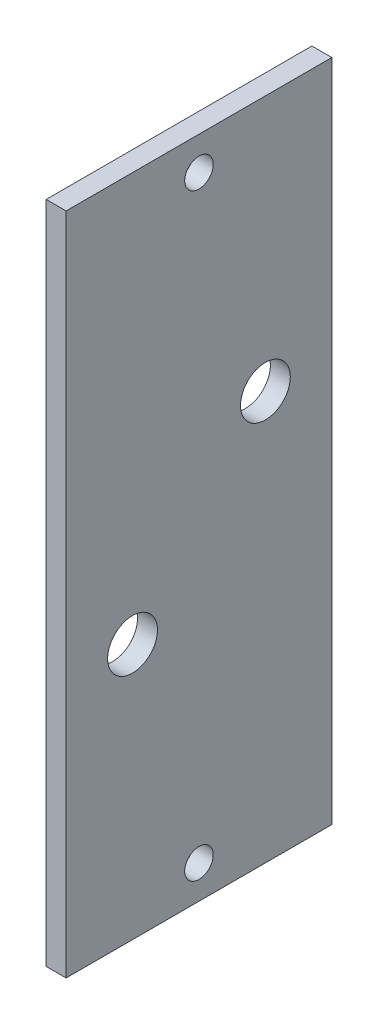
SolidWorks part; units mm, degrees
ref_plane "Front Plane" through (0, 0, 0) normal (0, 0, 1) x (1, 0, 0)
ref_plane "Top Plane" through (0, 0, 0) normal (0, 1, 0) x (1, 0, 0)
ref_plane "Right Plane" through (0, 0, 0) normal (1, 0, 0) x (0, 0, -1)
sketch "Sketch1" plane through (0, 0, 0) normal (1, 0, 0) x (0, 0, -1)
  line L0 (20, 100) -> (20, 0) construction
  line L1 (0, 0) -> (40, 0)
  line L2 (0, 0) -> (0, 100)
  line L3 (0, 100) -> (40, 100)
  line L4 (40, 0) -> (40, 100)
  line L5 (0, 50) -> (40, 50) construction
  circle A0 centre (20, 95) radius 2.15
  circle A1 centre (20, 5) radius 2.15
  circle A2 centre (10, 38.5) radius 3.75
  circle A3 centre (30, 61.5) radius 3.75
  dimension "D3" = 4.3
  dimension "D8" = 7.5
  dimension "D9" = 7.5
  dimension "D4" = 4.3
  dimension "D1" = 100
  dimension "D2" = 40
  dimension "D5" = 5
  dimension "D6" = 5
  dimension "D7" = 23
  dimension "D10" = 20
  dimension "D11" = 10
  dimension "D12" = 11.5
extrude "Boss-Extrude2" add sketch "Sketch1" along normal blind 3
equation "\"D9@Sketch1\"=\"D8@Sketch1\""
equation "\"D4@Sketch1\"=\"D3@Sketch1\""
